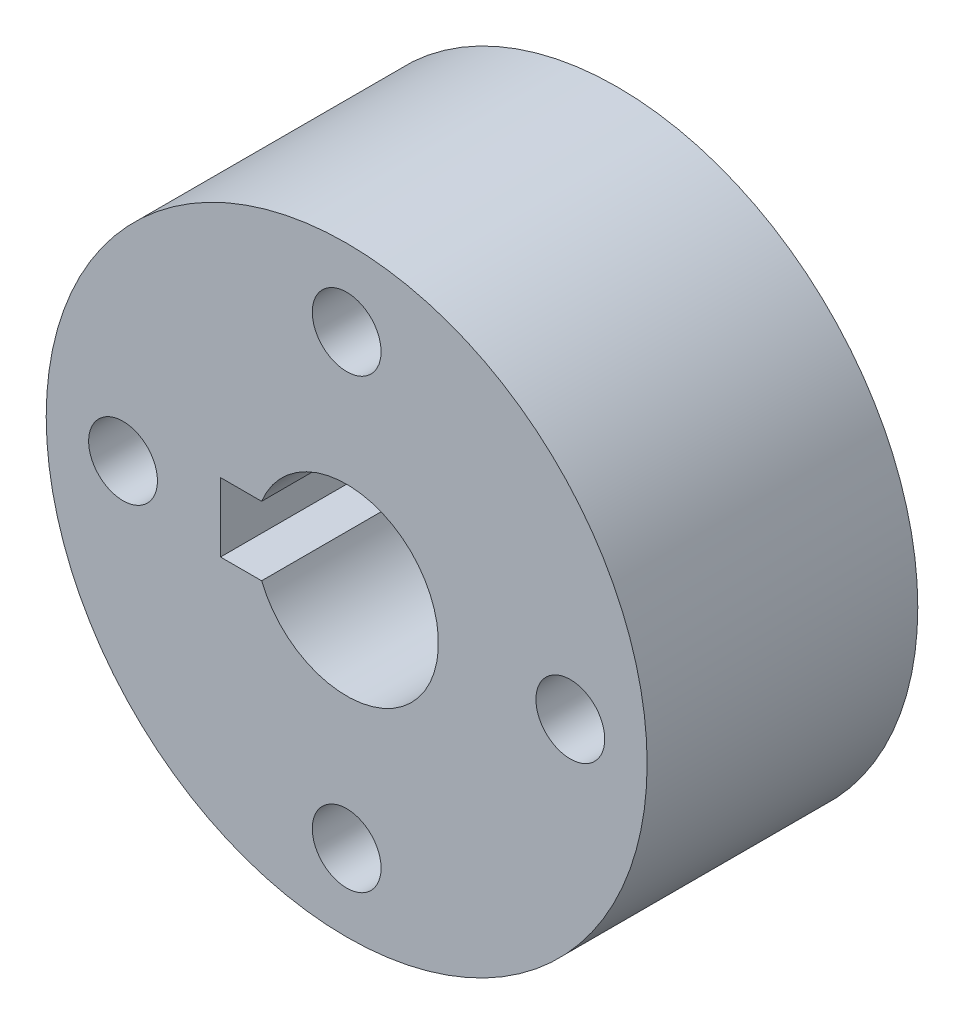
SolidWorks part; units mm, degrees
ref_plane "前视基准面" through (0, 0, 0) normal (0, 0, 1) x (1, 0, 0)
ref_plane "上视基准面" through (0, 0, 0) normal (0, 1, 0) x (1, 0, 0)
ref_plane "右视基准面" through (0, 0, 0) normal (1, 0, 0) x (0, 0, -1)
other "Configuration Table"
sketch "草图1" plane through (0, 0, 0) normal (0, 0, 1) x (1, 0, 0)
  circle A0 centre (0, 0) radius 13.1
  dimension "D1" = 26.2
extrude "凸台-拉伸1" add sketch "草图1" along normal blind 11.8
sketch "草图3" plane through (0, 0, 11.8) normal (0, 0, 1) x (1, 0, 0)
  circle A0 centre (0, 0) radius 9.75 construction
  circle A1 centre (-9.75, 0) radius 1.5
  circle A3 centre (0, 9.75) radius 1.5
  circle A4 centre (9.75, 0) radius 1.5
  circle A5 centre (0, -9.75) radius 1.5
  point P14 (0, 0)
  dimension "D1" = 19.5
  dimension "D2" = 3
  dimension "D3" = 4
extrude "切除-拉伸1" cut sketch "草图3" against normal blind 5
sketch "草图4" plane through (0, 0, 11.8) normal (0, 0, 1) x (1, 0, 0)
  line L0 (-5.5, -1.5) -> (-5.5, 1.5)
  line L1 (-6, 0) -> (49994, 0) construction
  line L2 (-5.5, 1.5) -> (-3.7081, 1.5)
  line L3 (-5.5, -1.5) -> (-3.7081, -1.5)
  circle A0 centre (-9.75, 0) radius 1.5
  circle A1 centre (9.75, 0) radius 1.5
  arc A2 (-3.7081, -1.5) -> (-3.7081, 1.5) centre (0, 0) ccw
  point P14 (-5.5, 0)
  dimension "D1" = 8
  dimension "D2" = 3
  dimension "D3" = 5.5
extrude "切除-拉伸2" cut sketch "草图4" against normal blind 15
